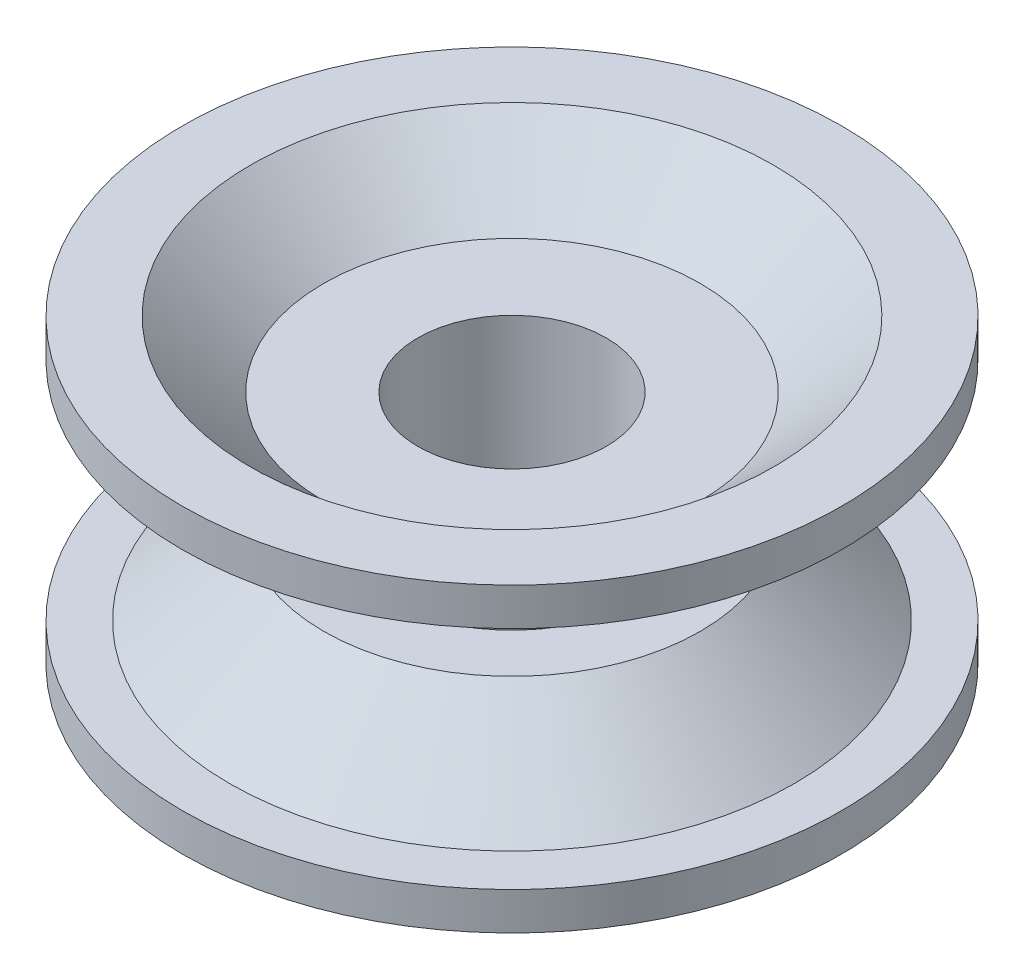
SolidWorks part; units mm, degrees
material "ABS"
ref_plane "Plan de face" through (0, 0, 0) normal (0, 0, 1) x (1, 0, 0)
ref_plane "Plan de dessus" through (0, 0, 0) normal (0, 1, 0) x (1, 0, 0)
ref_plane "Plan de droite" through (0, 0, 0) normal (1, 0, 0) x (0, 0, -1)
sketch "Esquisse1" plane through (0, 0, 0) normal (0, 0, 1) x (1, 0, 0)
  line L0 (0, 0) -> (0, 11.3816) construction
  line L1 (2.7778, -1.6) -> (3.5, -1.6)
  line L2 (3.5, -1.6) -> (3.5, -1.2)
  line L3 (3.5, -1.2) -> (3, -1.2)
  line L4 (3, -1.2) -> (2, -0.3)
  line L5 (2, -0.3) -> (1.4, -0.3)
  line L6 (1.4, -0.3) -> (1.4, 0.3)
  line L7 (1.4, 0.3) -> (2, 0.3)
  line L8 (2, 0.3) -> (3, 1.2)
  line L9 (3, 1.2) -> (3.5, 1.2)
  line L10 (3.5, 1.2) -> (3.5, 1.6)
  line L11 (3.5, 1.6) -> (2.7778, 1.6)
  line L12 (2.7778, 1.6) -> (2, 0.9)
  line L13 (2, 0.9) -> (1, 0.9)
  line L14 (1, 0.9) -> (1, -2.4)
  line L15 (1.4, 0) -> (24.6147, 0) construction
  line L16 (1, -2.4) -> (1.4, -2.4)
  line L17 (1.4, -2.4) -> (1.4, -0.9)
  line L18 (1.4, -0.9) -> (2, -0.9)
  line L19 (2, -0.9) -> (2.7778, -1.6)
  dimension "D1" = 0.4
  dimension "D2" = 0.6
  dimension "D3" = 3.2
  dimension "D4" = 7
  dimension "D5" = 2.8
  dimension "D6" = 4
  dimension "D7" = 6
  dimension "D8" = 0.7
  dimension "D9" = 4
  dimension "D10" = 2
  dimension "D11" = 4
revolve "Révolution1" add sketch "Esquisse1" angle 360 about L0
